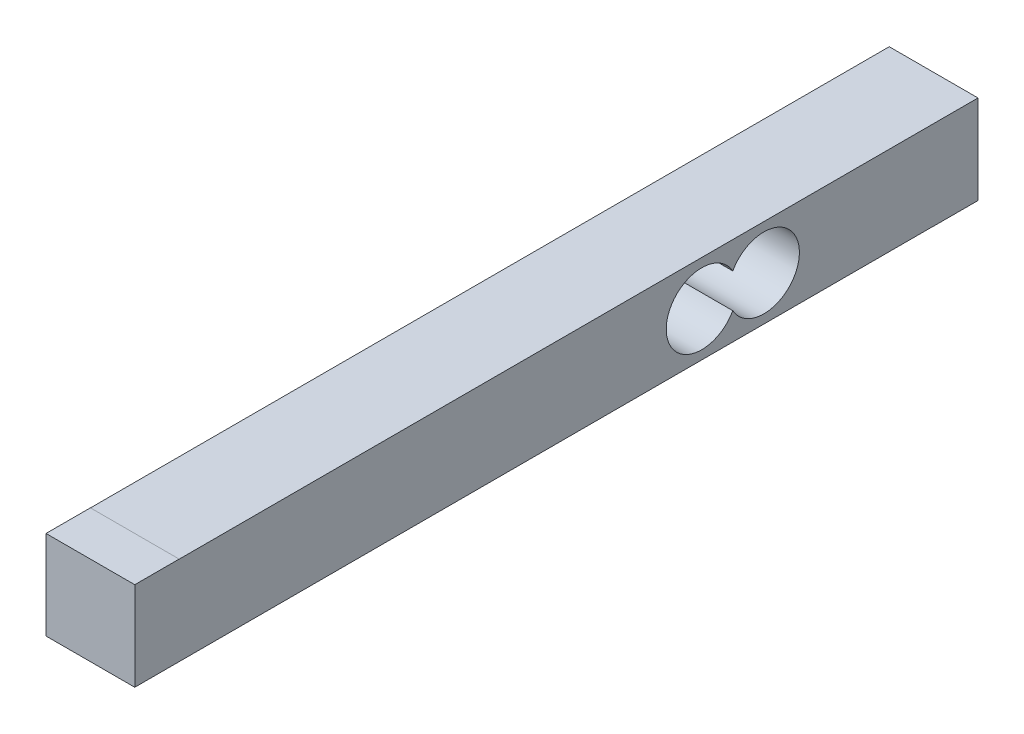
SolidWorks part; units mm, degrees
ref_plane "Plan de face" through (0, 0, 0) normal (0, 0, 1) x (1, 0, 0)
ref_plane "Plan de dessus" through (0, 0, 0) normal (0, 1, 0) x (1, 0, 0)
ref_plane "Plan de droite" through (0, 0, 0) normal (1, 0, 0) x (0, 0, -1)
sketch "Esquisse1" plane through (0, 0, 0) normal (0, 0, 1) x (1, 0, 0)
  line L1 (-5, 5) -> (5, 5)
  line L2 (-5, 5) -> (-5, -5)
  line L3 (-5, -5) -> (5, -5)
  line L4 (5, 5) -> (5, -5)
  dimension "D1" = 5
  dimension "D2" = 5
  dimension "D3" = 10
  dimension "D4" = 10
extrude "Boss.-Extru.1" add sketch "Esquisse1" along normal blind 95
sketch "Esquisse2" plane through (0, 5, 0) normal (0, 1, 0) x (1, 0, 0)
  line L0 (5, -95) -> (5, 0) construction
  line L1 (-5, -95) -> (5, -95)
  line L2 (-5, -95) -> (-5, -90)
  line L3 (-5, -90) -> (5, -90)
  line L4 (5, -95) -> (5, -90)
  dimension "D1" = 5
extrude "Boss.-Extru.2" add sketch "Esquisse2" along normal blind 0.01
sketch "Esquisse3" plane through (0, -5, 0) normal (0, -1, 0) x (1, 0, 0)
  line L0 (5, 95) -> (5, 0) construction
  line L1 (-5, 0) -> (5, 0)
  line L2 (-5, 0) -> (-5, 5)
  line L3 (-5, 5) -> (5, 5)
  line L4 (5, 0) -> (5, 5)
  dimension "D1" = 5
extrude "Boss.-Extru.3" add sketch "Esquisse3" along normal blind 0.01
sketch "Esquisse6" plane through (5, 0, 0) normal (1, 0, 0) x (0, 0, -1)
  line L0 (0, -0.005) -> (-60.3787, -0.005) construction
  line L1 (0, -5.01) -> (0, 5) construction
  arc A2 (-27.625, 1.9315) -> (-27.625, -1.9415) centre (-31.125, -0.005) ccw
  arc A3 (-27.625, -1.9415) -> (-27.625, 1.9315) centre (-24.125, -0.005) ccw
  dimension "D1" = 4
  dimension "D2" = 4
  dimension "D3" = 7
  dimension "D4" = 24.125
extrude "Enlèv. mat.-Extru.2" cut sketch "Esquisse6" against normal through all
